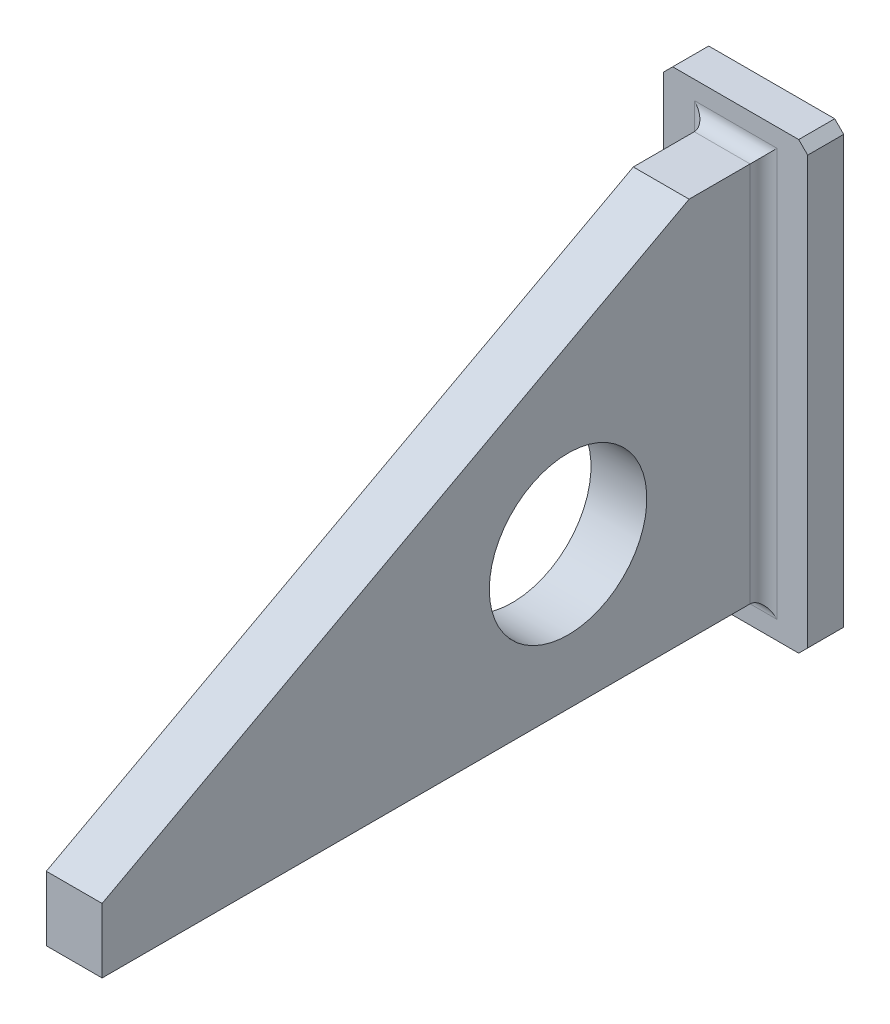
SolidWorks part; units mm, degrees
ref_plane "Front Plane" through (0, 0, 0) normal (0, 0, 1) x (1, 0, 0)
ref_plane "Top Plane" through (0, 0, 0) normal (0, 1, 0) x (1, 0, 0)
ref_plane "Right Plane" through (0, 0, 0) normal (1, 0, 0) x (0, 0, -1)
sketch "Sketch7" plane through (0, 0, 0) normal (1, 0, 0) x (0, 0, -1)
  line L11 (-21.0301, 104.9741) -> (-186.6706, 15.6835)
  line L12 (-186.6706, 15.6835) -> (-186.6706, -2.54)
  line L13 (-186.6706, -2.54) -> (2.54, -2.54)
  line L14 (2.54, -2.54) -> (2.54, 104.9741)
  line L15 (2.54, 104.9741) -> (-21.0301, 104.9741)
extrude "Extrude8" add sketch "Sketch7" along normal blind 15.748
sketch "Sketch8" plane through (0, 0, 0) normal (1, 0, 0) x (0, 0, -1)
  circle A0 centre (-55.1806, 37.7685) radius 22.225
  dimension "D1" = 44.45
extrude "Extrude10" cut sketch "Sketch8" along normal through all
sketch "Sketch9" plane through (0, 0, 0) normal (0, 0, 1) x (1, 0, 0)
  line L2 (-12.4418, 113.985) -> (28.1898, 113.985)
  line L3 (-12.4418, 113.985) -> (-12.4418, -11.5509)
  line L4 (-12.4418, -11.5509) -> (28.1898, -11.5509)
  line L5 (28.1898, 113.985) -> (28.1898, -11.5509)
  point P4 (7.874, 51.2171)
extrude "Extrude11" add sketch "Sketch9" against normal blind 10.16
chamfer "Chamfer1" distance 2.54 angle 45 4 edges at (28.1898, -11.5509, -5.08) (-12.4418, -11.5509, -5.08) (-12.4418, 113.985, -5.08) (28.1898, 113.985, -5.08)
fillet "Fillet2" radius 3.81 4 edges at (7.874, -2.54, 0) (0, 51.2171, 0) (7.874, 104.9741, 0) (15.748, 51.2171, 0)
